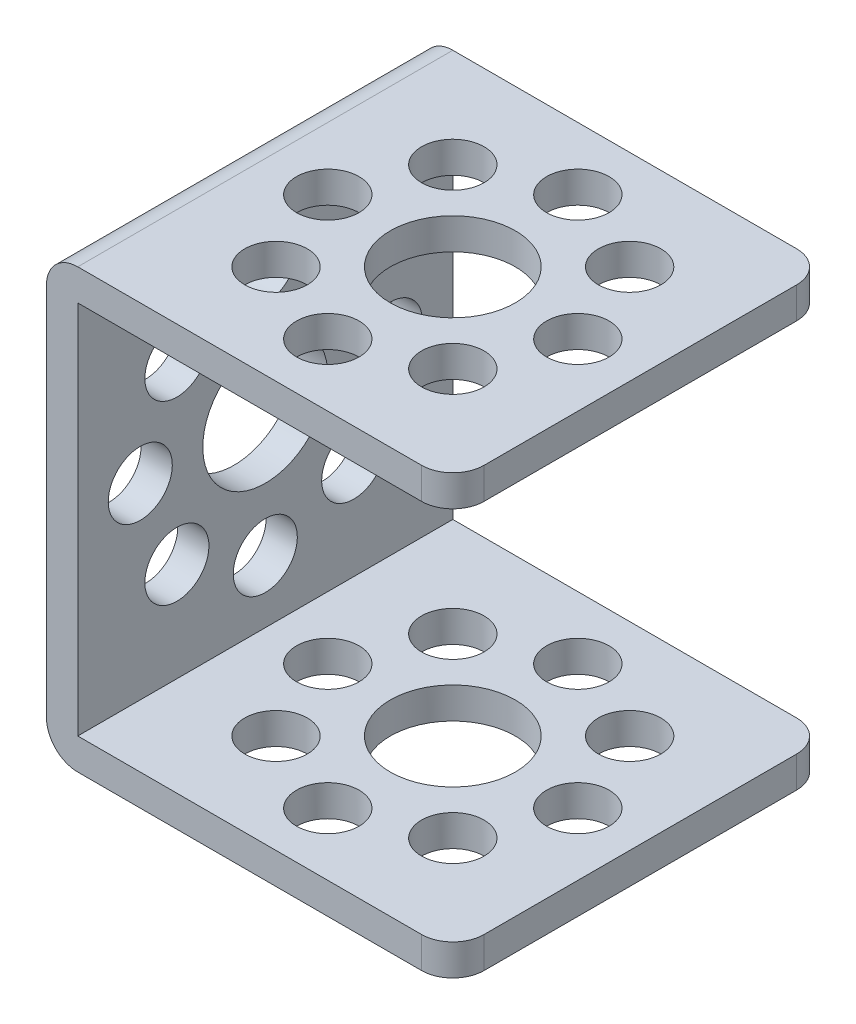
SolidWorks part; units mm, degrees
ref_plane "Front Plane" through (0, 0, 0) normal (0, 0, 1) x (1, 0, 0)
ref_plane "Top Plane" through (0, 0, 0) normal (0, 1, 0) x (1, 0, 0)
ref_plane "Right Plane" through (0, 0, 0) normal (1, 0, 0) x (0, 0, -1)
sketch "Sketch1" plane through (0, 0, 0) normal (0, 0, 1) x (1, 0, 0)
  line L0 (0, 0) -> (0, 26)
  line L2 (2, 26) -> (2, 2)
  line L3 (2, 2) -> (26, 2)
  line L4 (26, 2) -> (26, 0)
  line L5 (26, 0) -> (0, 0)
  line L7 (2, 26) -> (26, 26)
  line L8 (0, 26) -> (0, 28)
  line L9 (0, 28) -> (26, 28)
  line L10 (26, 26) -> (26, 28)
  point P10 (2, 26)
  point P11 (0, 27.9308)
  point P12 (25.9668, 27.7085)
  point P13 (26, 29.8091)
  point P14 (0, 0)
  dimension "D1" = 26
  dimension "D2" = 26
  dimension "D3" = 2
  dimension "D4" = 2
  dimension "D5" = 2
extrude "Boss-Extrude1" add sketch "Sketch1" along normal blind 24
sketch "Sketch2" plane through (2, 0, 0) normal (1, 0, 0) x (0, 0, -1)
  line L2 (0, 2) -> (0, 26) construction
  line L3 (-24, 26) -> (0, 26) construction
  circle A0 centre (-12, 22) radius 2.05
  circle A1 centre (-12, 14) radius 4
  circle A2 centre (-12, 14) radius 8 construction
  circle A3 centre (-6.3431, 19.6569) radius 2.05
  circle A4 centre (-4, 14) radius 2.05
  circle A5 centre (-6.3431, 8.3431) radius 2.05
  circle A6 centre (-12, 6) radius 2.05
  circle A7 centre (-17.6569, 8.3431) radius 2.05
  circle A8 centre (-20, 14) radius 2.05
  circle A9 centre (-17.6569, 19.6569) radius 2.05
  point P4 (-19.0313, 17.8159)
  point P8 (0, 0)
  point P14 (0, 0)
  point P29 (-12, 14)
  dimension "D1" = 4.1
  dimension "D2" = 8
  dimension "D3" = 16
  dimension "D4" = 12
  dimension "D6" = 12
  dimension "D7" = 8
extrude "Cut-Extrude1" cut sketch "Sketch2" against normal through all
sketch "Sketch3" plane through (0, 2, 0) normal (0, 1, 0) x (1, 0, 0)
  line L2 (26, -24) -> (26, 0) construction
  line L4 (26, 0) -> (2, 0) construction
  circle A0 centre (14, -12) radius 4
  circle A1 centre (14, -12) radius 8 construction
  circle A2 centre (22, -12) radius 2
  circle A3 centre (19.6569, -17.6569) radius 2
  circle A4 centre (14, -20) radius 2
  circle A5 centre (8.3431, -17.6569) radius 2
  circle A6 centre (6, -12) radius 2
  circle A7 centre (8.3431, -6.3431) radius 2
  circle A8 centre (14, -4) radius 2
  circle A9 centre (19.6569, -6.3431) radius 2
  point P10 (14, -12)
  point P11 (14, -12)
  point P25 (14, -12)
  dimension "D1" = 8
  dimension "D4" = 16
  dimension "D5" = 4
  dimension "D2" = 12
  dimension "D3" = 12
  dimension "D6" = 8
extrude "Cut-Extrude2" cut sketch "Sketch3" against normal through all both and the other way through all
fillet "Fillet1" radius 2 6 edges at (26, 1, 0) (26, 1, 24) (0, 0, 12) (0, 28, 12) (26, 27, 24) (26, 27, 0)
